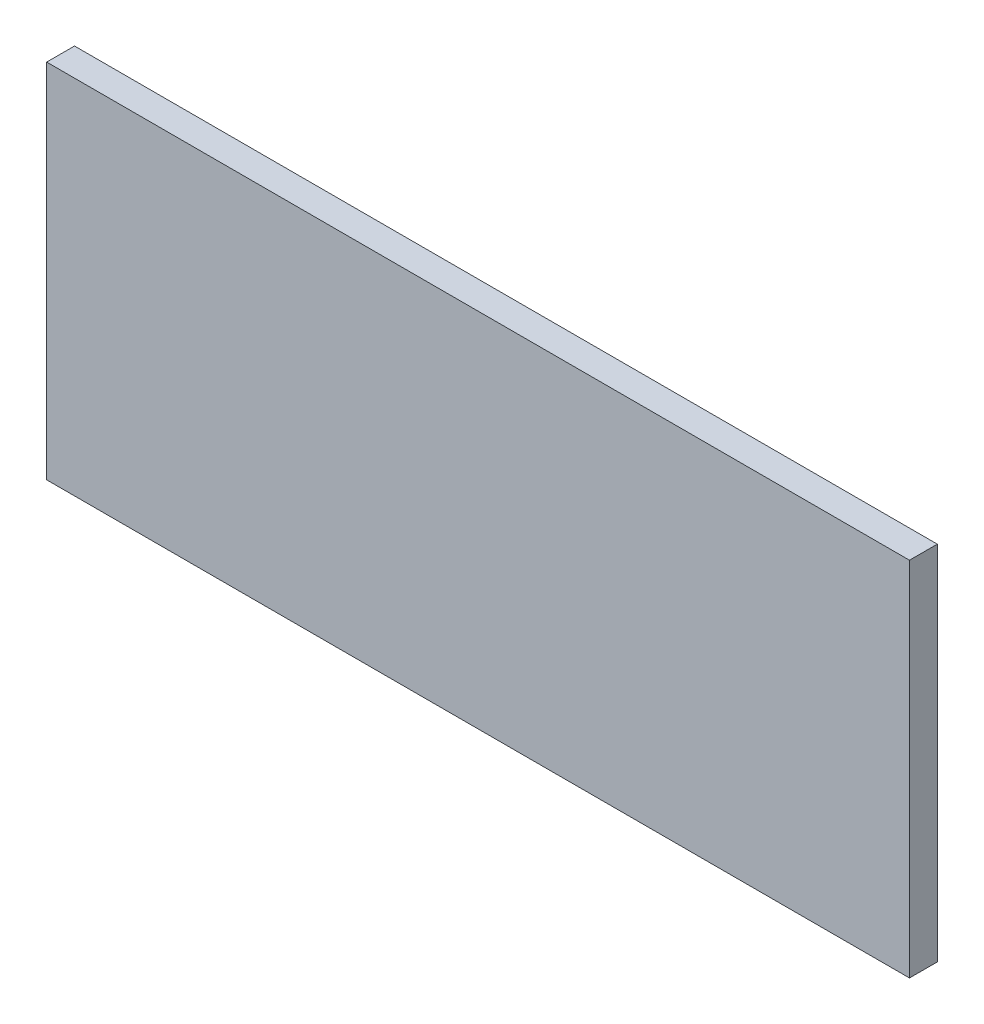
SolidWorks part; units mm, degrees
ref_plane "前视基准面" through (0, 0, 0) normal (0, 0, 1) x (1, 0, 0)
ref_plane "上视基准面" through (0, 0, 0) normal (0, 1, 0) x (1, 0, 0)
ref_plane "右视基准面" through (0, 0, 0) normal (1, 0, 0) x (0, 0, -1)
other "Configuration Table"
sketch "草图1" plane through (0, 0, 0) normal (0, 0, 1) x (1, 0, 0)
  line L1 (-310, -130) -> (310, -130)
  line L2 (-310, -130) -> (-310, 130)
  line L3 (-310, 130) -> (310, 130)
  line L4 (310, -130) -> (310, 130)
  line L5 (-310, -130) -> (310, 130) construction
  line L6 (-310, 130) -> (310, -130) construction
  point P0 (0, 0)
extrude "凸台-拉伸1" add sketch "草图1" along normal blind 20
